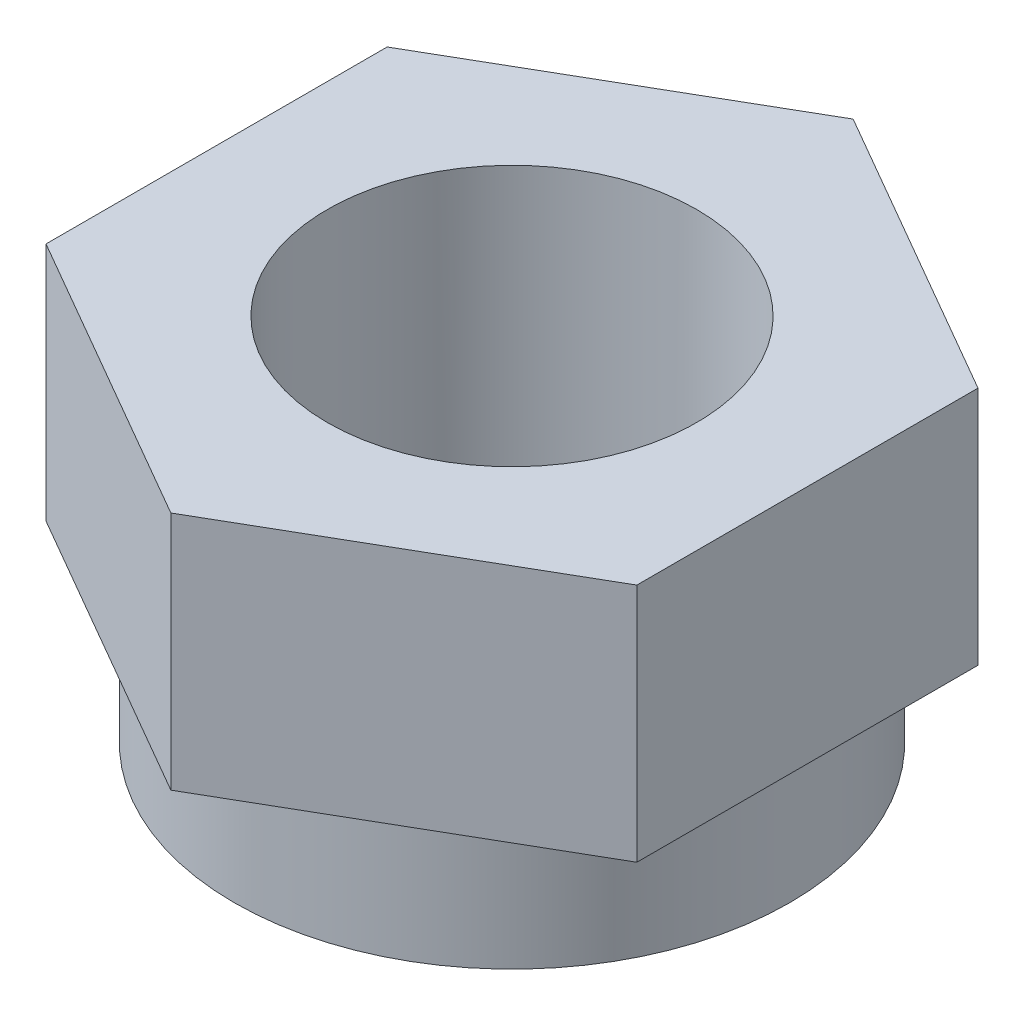
SolidWorks part; units mm, degrees
ref_plane "Front Plane" through (0, 0, 0) normal (0, 0, 1) x (1, 0, 0)
ref_plane "Top Plane" through (0, 0, 0) normal (0, 1, 0) x (1, 0, 0)
ref_plane "Right Plane" through (0, 0, 0) normal (1, 0, 0) x (0, 0, -1)
sketch "Sketch1" plane through (0, 0, 0) normal (0, 1, 0) x (1, 0, 0)
  line L0 (4, -2.3094) -> (0, -4.6188)
  line L1 (0, -4.6188) -> (-4, -2.3094)
  line L2 (-4, -2.3094) -> (-4, 2.3094)
  line L3 (-4, 2.3094) -> (0, 4.6188)
  line L4 (0, 4.6188) -> (4, 2.3094)
  line L5 (4, 2.3094) -> (4, -2.3094)
extrude "Boss-Extrude1" add sketch "Sketch1" against normal blind 3.25
ref_plane "Plane1" through (0, -3.25, 0) normal (0, 1, 0) x (1, 0, 0)
sketch "Sketch2" plane through (0, -3.25, 0) normal (0, 1, 0) x (1, 0, 0)
  circle A0 centre (0, 0) radius 3.76
extrude "Boss-Extrude2" add sketch "Sketch2" against normal blind 1.75
sketch "Sketch3" plane through (0, 0, 0) normal (0, 1, 0) x (1, 0, 0)
  circle A0 centre (0, 0) radius 2.5
extrude "Cut-Extrude1" cut sketch "Sketch3" against normal through all and the other way through all
cosmetic thread "Cosmetic Thread1" parameters "D1"=5, "D2"=5.5
